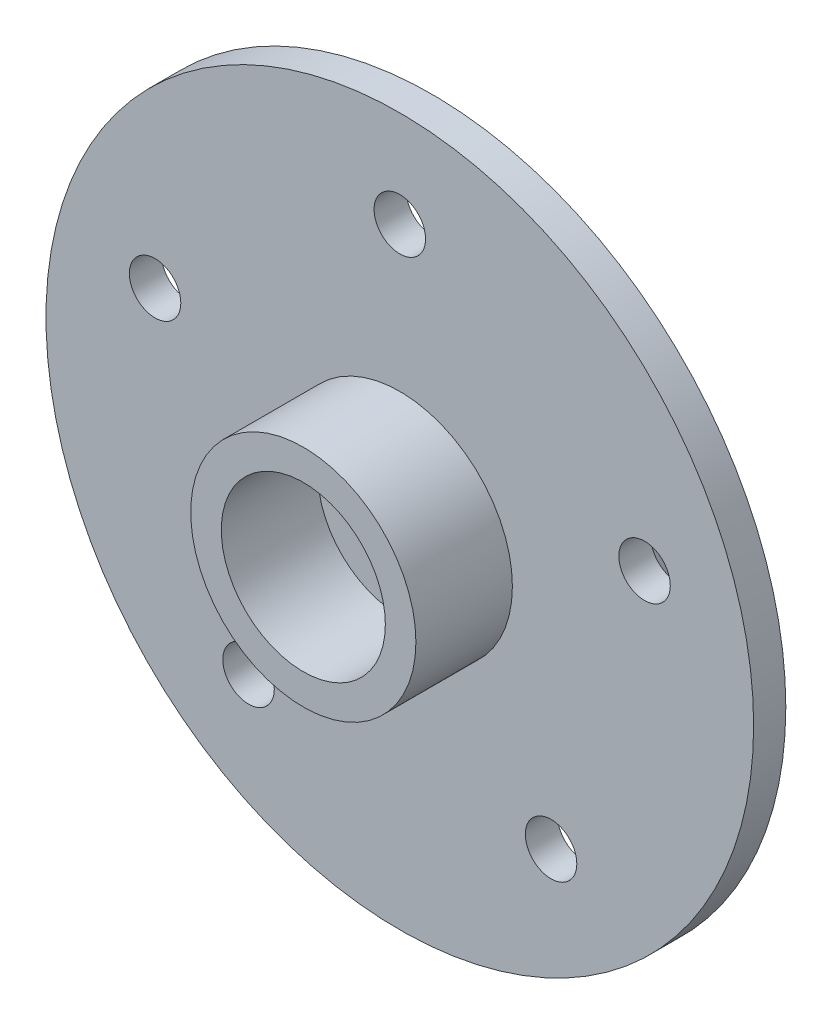
SolidWorks part; units mm, degrees
ref_plane "前视基准面" through (0, 0, 0) normal (0, 0, 1) x (1, 0, 0)
ref_plane "上视基准面" through (0, 0, 0) normal (0, 1, 0) x (1, 0, 0)
ref_plane "右视基准面" through (0, 0, 0) normal (1, 0, 0) x (0, 0, -1)
other "Configuration Table"
sketch "草图1" plane through (0, 0, 0) normal (0, 0, 1) x (1, 0, 0)
  circle A4 centre (0, 0) radius 3.1
  circle A5 centre (0, 0) radius 22
  circle A6 centre (0, 0) radius 16 construction
  circle A8 centre (0, 16) radius 1.6
  circle A9 centre (15.2169, 4.9443) radius 1.6
  circle A10 centre (9.4046, -12.9443) radius 1.6
  circle A11 centre (-9.4046, -12.9443) radius 1.6
  circle A12 centre (-15.2169, 4.9443) radius 1.6
  point P0 (0, 0)
  point P17 (0, 0)
  point P19 (0, 0)
  dimension "D3" = 5
  dimension "D1" = 44
  dimension "D2" = 32
  dimension "D4" = 6.2
extrude "凸台-拉伸1" add sketch "草图1" along normal blind 2
sketch "草图2" plane through (0, 0, 2) normal (0, 0, 1) x (1, 0, 0)
  circle A0 centre (0, 0) radius 7
  circle A1 centre (0, 0) radius 5.1
  dimension "D1" = 14
  dimension "D2" = 10.2
sketch "草图3" plane through (0, 0, 0) normal (0, 0, -1) x (-1, 0, 0)
  circle A0 centre (0, 0) radius 11
  circle A1 centre (0, 0) radius 7.6
  dimension "D1" = 22
  dimension "D2" = 15.2
extrude "凸台-拉伸2" add sketch "草图3" along normal blind 5
extrude "凸台-拉伸3" add sketch "草图2" along normal blind 6
